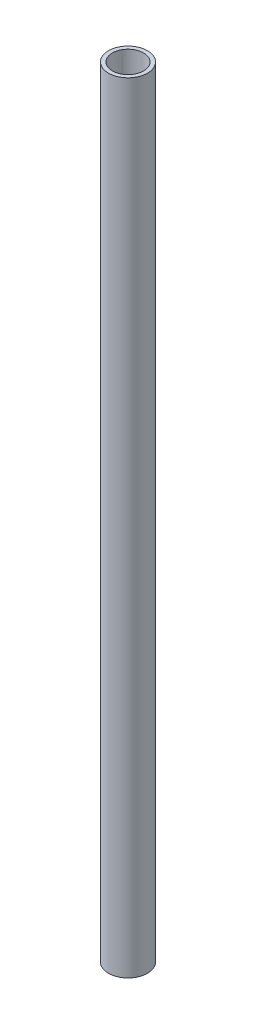
SolidWorks part; units mm, degrees
ref_plane "Front Plane" through (0, 0, 0) normal (0, 0, 1) x (1, 0, 0)
ref_plane "Top Plane" through (0, 0, 0) normal (0, 1, 0) x (1, 0, 0)
ref_plane "Right Plane" through (0, 0, 0) normal (1, 0, 0) x (0, 0, -1)
sketch "Sketch1" plane through (0, 0, 0) normal (0, 1, 0) x (1, 0, 0)
  circle A0 centre (0, 0) radius 2
  circle A1 centre (0, 0) radius 2.5
  dimension "D1" = 4
  dimension "D2" = 5
extrude "Boss-Extrude1" add sketch "Sketch1" along normal blind 100
